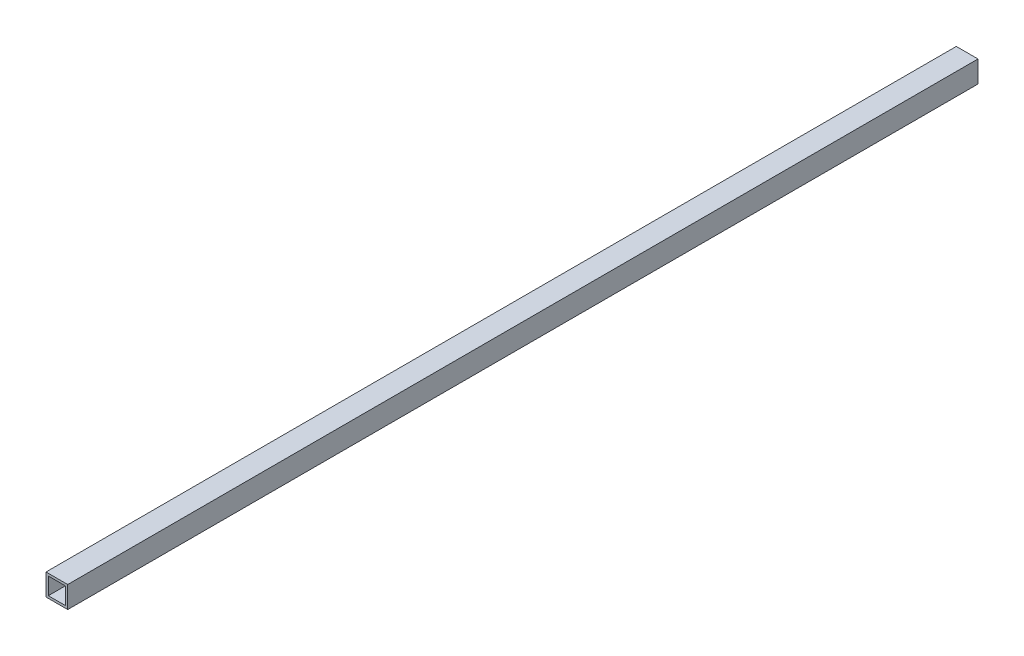
SolidWorks part; units mm, degrees
ref_plane "前视基准面" through (0, 0, 0) normal (0, 0, 1) x (1, 0, 0)
ref_plane "上视基准面" through (0, 0, 0) normal (0, 1, 0) x (1, 0, 0)
ref_plane "右视基准面" through (0, 0, 0) normal (1, 0, 0) x (0, 0, -1)
sketch "草图1" plane through (0, 0, 0) normal (0, 0, 1) x (1, 0, 0)
  line L1 (-5.5, 5.5) -> (5.5, 5.5)
  line L2 (-5.5, 5.5) -> (-5.5, -5.5)
  line L3 (-5.5, -5.5) -> (5.5, -5.5)
  line L4 (5.5, 5.5) -> (5.5, -5.5)
  line L5 (-5.5, 5.5) -> (5.5, -5.5) construction
  line L6 (-5.5, -5.5) -> (5.5, 5.5) construction
  point P0 (0, 0)
  dimension "D1" = 11
extrude "拉伸-薄壁1" add sketch "草图1" along normal blind 587 thin thin type one direction wall 1.5
